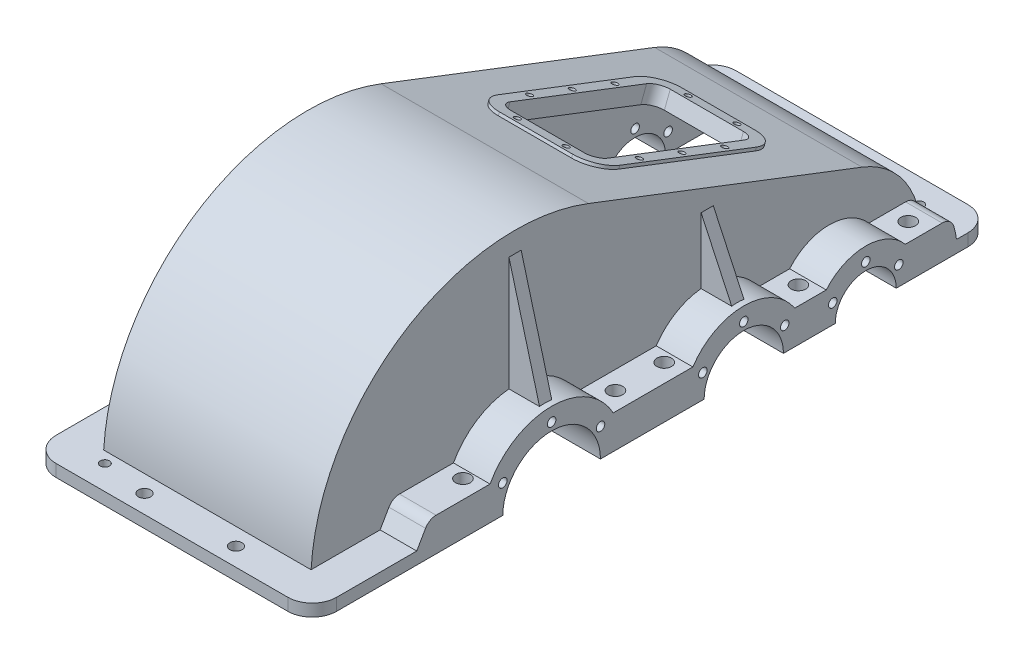
SolidWorks part; units mm, degrees
material "Cast Alloy Steel"
ref_plane "Front Plane" through (0, 0, 0) normal (0, 0, 1) x (1, 0, 0)
ref_plane "Top Plane" through (0, 0, 0) normal (0, 1, 0) x (1, 0, 0)
ref_plane "Right Plane" through (0, 0, 0) normal (1, 0, 0) x (0, 0, -1)
sketch "Sketch1" plane through (0, 0, 0) normal (1, 0, 0) x (0, 0, -1)
  line L0 (-500, 0) -> (500, 0)
  line L1 (403.8835, 139.9877) -> (-44.6602, 312.6393)
  arc A0 (500, 0) -> (403.8835, 139.9877) centre (350, 0) ccw
  arc A1 (-44.6602, 312.6393) -> (-500, 0) centre (-165, 0) ccw
  point P7 (0, 0)
  point P8 (436.4106, 249.0469)
  point P9 (0, 0)
  point P10 (0, 0)
  dimension "D3" = 150
  dimension "D4" = 335
  dimension "D1" = 165
  dimension "D2" = 350
extrude "Boss-Extrude1" add sketch "Sketch1" along normal mid plane 340
shell "Shell1" thickness 21.8
sketch "Sketch2" plane through (0, 0, 0) normal (0, -1, 0) x (1, 0, 0)
  line L0 (-148.2, 478.2) -> (-148.2, -478.2) construction
  line L1 (-230, -557.5) -> (230, -557.5)
  line L2 (-230, -557.5) -> (-230, 557.5)
  line L3 (-230, 557.5) -> (230, 557.5)
  line L4 (230, -557.5) -> (230, 557.5)
  line L5 (-230, -557.5) -> (230, 557.5) construction
  line L6 (-230, 557.5) -> (230, -557.5) construction
  line L7 (148.2, 478.2) -> (148.2, -478.2) construction
  line L8 (148.2, -478.2) -> (-148.2, -478.2) construction
  line L9 (148.2, 478.2) -> (-148.2, 478.2) construction
  line L10 (-148.2, 478.2) -> (-148.2, -478.2)
  line L11 (148.2, 478.2) -> (148.2, -478.2)
  line L12 (148.2, -478.2) -> (-148.2, -478.2)
  line L13 (148.2, 478.2) -> (-148.2, 478.2)
  point P0 (0, 0)
  line M3 (-170, 500) -> (-170, -500)
  line M4 (-170, -500) -> (170, -500)
  line M5 (170, -500) -> (170, 500)
  line M6 (170, 500) -> (-170, 500)
  line M7 (-148.2, -478.2) -> (-148.2, 478.2)
  line M8 (-148.2, 478.2) -> (148.2, 478.2)
  line M9 (148.2, 478.2) -> (148.2, -478.2)
  line M10 (148.2, -478.2) -> (-148.2, -478.2)
  dimension "D1" = 1115
  dimension "D2" = 460
extrude "Boss-Extrude4" add sketch "Sketch2" against normal blind 20 contours M6 M3 M4 M5 M10 M7 M8 M9 | L1 L4 L3 L2 M3 M6 M5 M4
fillet "Fillet1" radius 40 4 edges at (-230, 10, -557.5) (-230, 10, 557.5) (230, 10, -557.5) (230, 10, 557.5)
sketch "Sketch6" plane through (0, 0, 0) normal (1, 0, 0) x (0, 0, -1)
  line L0 (517.5, 0) -> (-517.5, 0) construction
  circle A0 centre (-165, 0) radius 80
  circle A1 centre (150, 0) radius 65
  circle A2 centre (350, 0) radius 50
  dimension "D1" = 160
  dimension "D2" = 130
  dimension "D3" = 100
  dimension "D4" = 165
  dimension "D5" = 350
  dimension "D6" = 200
extrude "Cut-Extrude2" cut sketch "Sketch6" against normal through all both and the other way through all
sketch "Sketch7" plane through (0, 0, 0) normal (1, 0, 0) x (0, 0, -1)
  line L0 (395.8258, 20) -> (498.6607, 20) construction
  line L1 (211.8466, 20) -> (304.1742, 20) construction
  line L2 (88.1534, 20) -> (-87.5403, 20) construction
  line L3 (-499.4025, 20) -> (-242.4597, 20) construction
  line L4 (395.8258, 20) -> (498.6607, 20)
  line L5 (211.8466, 20) -> (304.1742, 20)
  line L6 (88.1534, 20) -> (-87.5403, 20)
  line L7 (-386.2023, 20) -> (-242.4597, 20)
  line L8 (-365.995, 55) -> (-265.995, 55)
  line L9 (66.4835, 55) -> (-64.005, 55)
  line L10 (233.5165, 55) -> (285.1926, 55)
  line L11 (414.8074, 55) -> (489.5529, 55)
  line L12 (-365.995, 55) -> (-386.2023, 20)
  line L13 (-499.4025, 55) -> (-265.995, 55) construction
  line L14 (-499.4025, 20) -> (-242.4597, 20) construction
  line L15 (414.8074, 55) -> (498.6607, 55) construction
  line L16 (-242.4597, 20) -> (-517.5, 20) construction
  arc A0 (498.6607, 20) -> (403.8835, 139.9877) centre (350, 0) ccw construction
  arc A1 (395.8258, 20) -> (304.1742, 20) centre (350, 0) ccw construction
  arc A2 (211.8466, 20) -> (88.1534, 20) centre (150, 0) ccw construction
  arc A3 (-87.5403, 20) -> (-242.4597, 20) centre (-165, 0) ccw construction
  arc A4 (498.6607, 20) -> (489.5529, 55) centre (350, 0) ccw
  arc A5 (395.8258, 20) -> (304.1742, 20) centre (350, 0) ccw
  arc A6 (211.8466, 20) -> (88.1534, 20) centre (150, 0) ccw
  arc A7 (-87.5403, 20) -> (-242.4597, 20) centre (-165, 0) ccw
  arc A8 (-64.005, 55) -> (-265.995, 55) centre (-165, 0) ccw
  arc A9 (233.5165, 55) -> (66.4835, 55) centre (150, 0) ccw
  arc A10 (414.8074, 55) -> (285.1926, 55) centre (350, 0) ccw
  point P26 (-394.0327, 20)
  dimension "D2" = 60
  dimension "D3" = 100
  dimension "D1" = 35
extrude "Boss-Extrude5" add sketch "Sketch7" against normal up to surface (60 mm away) from surface at 230 up to face at (170, 87.5999, -97.0662) starting at face at (230, 10.051, -0.1155)
sketch "Sketch8" plane through (0, 20, 0) normal (0, 1, 0) x (1, 0, 0)
  line L0 (200, 524.3283) -> (200, -465.5786) construction
  line L1 (230, 414.8074) -> (230, 489.5529) construction
  line L3 (170, 489.5529) -> (230, 489.5529) construction
  circle A0 centre (200, 449.5529) radius 12
  circle A1 centre (200, 269.5529) radius 12
  circle A2 centre (200, 49.5529) radius 12
  circle A3 centre (200, -30.4471) radius 12
  circle A4 centre (200, -280.4471) radius 12
  dimension "D3" = 24
  dimension "D5" = 24
  dimension "D6" = 24
  dimension "D8" = 24
  dimension "D10" = 24
  dimension "D1" = 30
  dimension "D2" = 40
  dimension "D4" = 180
  dimension "D7" = 220
  dimension "D9" = 80
  dimension "D11" = 250
extrude "Cut-Extrude3" cut sketch "Sketch8" against normal up to surface (20 mm away) and the other way through all up to face at (189.1, 0, -257.5)
fillet "Fillet2" radius 20 2 edges at (200, 55, -489.5529) (200, 55, 365.995)
sketch "Sketch9" plane through (0, 20, 0) normal (0, 1, 0) x (1, 0, 0)
  line L0 (75, 527.5) -> (75, -527.5) construction
  line L1 (-190, 557.5) -> (190, 557.5) construction
  line L2 (-190, -557.5) -> (190, -557.5) construction
  circle A0 centre (75, 527.5) radius 10
  circle A1 centre (75, -527.5) radius 10
  dimension "D4" = 20
  dimension "D1" = 75
  dimension "D2" = 30
  dimension "D3" = 30
extrude "Cut-Extrude4" cut sketch "Sketch9" against normal up to surface (20 mm away) up to face at (200, 0, -257.5529)
sketch "Sketch10" plane through (0, 20, 0) normal (0, 1, 0) x (1, 0, 0)
  line L0 (230, 517.5) -> (230, 498.6607) construction
  line L1 (-190, 557.5) -> (190, 557.5) construction
  circle A0 centre (150, 517.5) radius 7.5
  circle A1 centre (-150, -517.5) radius 7.5
  point P11 (0, 0)
  dimension "D1" = 15
  dimension "D2" = 80
  dimension "D3" = 40
  dimension "D4" = 2
sketch "Sketch11" plane through (0, 0, 0) normal (0, 1, 0) x (1, 0, 0)
  line L0 (0, 0) -> (-447.3821, 0)
  line L2 (0, 626.9048) -> (-421.736, 626.9048)
  line L3 (0, 626.9048) -> (0, -604.1083)
  line L4 (0, -604.1083) -> (-421.736, -604.1083)
  line L5 (-421.736, 626.9048) -> (-421.736, -604.1083)
extrude "Cut-Extrude6" cut sketch "Sketch11" against normal through all both and the other way through all contours L2 L5 L0 L3 | L0 L5 L4 L3
mirror "Mirror1" about plane through (0, 0, 0) normal (-1, 0, 0) of bodies 114
extrude "Cut-Extrude7" cut sketch "Sketch10" against normal through all both and the other way through all
sketch "Sketch12" plane through (230, 0, 0) normal (1, 0, 0) x (0, 0, -1)
  circle A0 centre (-165, 0) radius 92.5 construction
  circle A1 centre (150, 0) radius 77.5 construction
  circle A2 centre (350, 0) radius 62.5 construction
  circle A3 centre (-165, 92.5) radius 7
  circle A4 centre (-84.8927, 46.25) radius 7
  circle A5 centre (-84.8927, -46.25) radius 7
  circle A6 centre (-165, -92.5) radius 7
  circle A7 centre (-245.1073, -46.25) radius 7
  circle A8 centre (-245.1073, 46.25) radius 7
  circle A9 centre (150, 77.5) radius 7
  circle A10 centre (217.117, 38.75) radius 7
  circle A11 centre (217.117, -38.75) radius 7
  circle A12 centre (150, -77.5) radius 7
  circle A13 centre (82.883, -38.75) radius 7
  circle A14 centre (82.883, 38.75) radius 7
  circle A15 centre (350, 62.5) radius 7
  circle A16 centre (404.1266, 31.25) radius 7
  circle A17 centre (404.1266, -31.25) radius 7
  circle A18 centre (350, -62.5) radius 7
  circle A19 centre (295.8734, -31.25) radius 7
  circle A20 centre (295.8734, 31.25) radius 7
  point P24 (-165, 0)
  point P37 (150, 0)
  point P50 (350, 0)
  dimension "D1" = 185
  dimension "D2" = 155
  dimension "D3" = 125
  dimension "D4" = 14
  dimension "D6" = 14
  dimension "D8" = 14
  dimension "D5" = 6
  dimension "D7" = 6
  dimension "D9" = 6
extrude "Cut-Extrude8" cut sketch "Sketch12" against normal through all both and the other way through all
ref_plane "Plane1" through (0, 0, 165) normal (0, 0, 1) x (1, 0, 0)
ref_plane "Plane2" through (0, 0, -150) normal (0, 0, 1) x (1, 0, 0)
sketch "Sketch13" plane through (0, 0, 165) normal (0, 0, 1) x (1, 0, 0)
  line L0 (220, 115) -> (170, 301.6025)
  line L1 (230, 115) -> (170, 115) construction
  line L2 (170, 20) -> (170, 335) construction
  line L3 (230, 55) -> (230, 115) construction
  dimension "D1" = 10
  dimension "D2" = 75
rib "Rib1" sketch "Sketch13" sketch "Sketch13" thickness 20 extrusion direction parallel to sketch draft on no parameters "D1"=20
sketch "Sketch14" plane through (0, 0, -150) normal (0, 0, 1) x (1, 0, 0)
  line L0 (220, 100) -> (169.7975, 207.6595)
  line L1 (230, 100) -> (170, 100) construction
  point P5 (0, 0)
  dimension "D1" = 10
  dimension "D2" = 65
rib "Rib2" sketch "Sketch14" sketch "Sketch14" thickness 20 extrusion direction parallel to sketch draft on no parameters "D1"=20
mirror "Mirror2" about plane through (0, 0, 0) normal (1, 0, 0) of "Rib2", "Rib1"
sketch "Sketch15" plane through (0, 257.3238, -99.048) normal (0, 0.9333, -0.3592) x (1, 0, 0)
  line L0 (0, 326.6381) -> (0, -153.9865) construction
  line L1 (170, 326.6381) -> (-170, 326.6381) construction
  line L2 (170, -153.9865) -> (-170, -153.9865) construction
  line L3 (170, 94.229) -> (-170, 94.229) construction
  line L4 (170, 74.8801) -> (170, 113.578) construction
  line L5 (-170, 113.578) -> (-170, 74.8801) construction
  line L7 (-80, -45.771) -> (80, -45.771)
  line L8 (-80, -45.771) -> (-80, 234.229)
  line L9 (-80, 234.229) -> (80, 234.229)
  line L10 (80, -45.771) -> (80, 234.229)
  line L11 (-80, -45.771) -> (80, 234.229) construction
  line L12 (-80, 234.229) -> (80, -45.771) construction
  point P12 (0, 94.229)
  dimension "D1" = 160
  dimension "D2" = 280
extrude "Cut-Extrude9" cut sketch "Sketch15" against normal up to surface and the other way through all
fillet "Fillet3" radius 20 4 edges at (80, 263.5933, -52.4166) (-80, 263.5933, -52.4166) (80, 163.0108, -313.7271) (-80, 163.0108, -313.7271)
sketch "Sketch17" plane through (0, 257.3238, -99.048) normal (0, 0.9333, -0.3592) x (1, 0, 0)
  line L0 (-80, -25.771) -> (-80, 214.229) construction
  line L1 (80, 214.229) -> (80, -25.771) construction
  line L3 (60, -45.771) -> (-60, -45.771) construction
  line L4 (-60, 234.229) -> (60, 234.229) construction
  line L5 (-80, -25.771) -> (-80, 214.229)
  line L6 (60, -45.771) -> (-60, -45.771)
  line L7 (80, 214.229) -> (80, -25.771)
  line L8 (-60, 234.229) -> (60, 234.229)
  line L9 (-100, -25.771) -> (-100, 214.229)
  line L10 (-60, 254.229) -> (60, 254.229)
  line L11 (100, 214.229) -> (100, -25.771)
  line L12 (60, -65.771) -> (-60, -65.771)
  arc A0 (-60, 234.229) -> (-80, 214.229) centre (-60, 214.229) ccw construction
  arc A1 (-80, -25.771) -> (-60, -45.771) centre (-60, -25.771) ccw construction
  arc A2 (60, -45.771) -> (80, -25.771) centre (60, -25.771) ccw construction
  arc A3 (80, 214.229) -> (60, 234.229) centre (60, 214.229) ccw construction
  arc A4 (-60, 234.229) -> (-80, 214.229) centre (-60, 214.229) ccw
  arc A5 (-80, -25.771) -> (-60, -45.771) centre (-60, -25.771) ccw
  arc A6 (60, -45.771) -> (80, -25.771) centre (60, -25.771) ccw
  arc A7 (80, 214.229) -> (60, 234.229) centre (60, 214.229) ccw
  arc A8 (-60, 254.229) -> (-100, 214.229) centre (-60, 214.229) ccw
  arc A9 (100, 214.229) -> (60, 254.229) centre (60, 214.229) ccw
  arc A10 (60, -65.771) -> (100, -25.771) centre (60, -25.771) ccw
  arc A11 (-100, -25.771) -> (-60, -65.771) centre (-60, -25.771) ccw
  dimension "D1" = 20
extrude "Boss-Extrude6" add sketch "Sketch17" along normal blind 5
sketch "Sketch18" plane through (0, 261.99, -100.8441) normal (0, 0.9333, -0.3592) x (1, 0, 0)
  line L20 (0, -129.0902) -> (0, 317.5483) construction
  line L21 (0, 94.229) -> (90, 94.229) construction
  line L24 (-60, -55.771) -> (60, -55.771)
  line L25 (90, -25.771) -> (90, 214.229)
  line L26 (60, 244.229) -> (-60, 244.229)
  line L27 (-90, 214.229) -> (-90, -25.771)
  line L28 (-60, -55.771) -> (60, -55.771) construction
  line L29 (90, -25.771) -> (90, 214.229) construction
  line L30 (60, 244.229) -> (-60, 244.229) construction
  line L31 (-90, 214.229) -> (-90, -25.771) construction
  circle A16 centre (40, 244.229) radius 5
  circle A17 centre (90, 169.229) radius 5
  circle A18 centre (90, 94.229) radius 5
  circle A19 centre (90, 19.229) radius 5
  arc A20 (-90, -25.771) -> (-60, -55.771) centre (-60, -25.771) ccw
  arc A21 (60, -55.771) -> (90, -25.771) centre (60, -25.771) ccw
  arc A22 (90, 214.229) -> (60, 244.229) centre (60, 214.229) ccw
  arc A23 (-60, 244.229) -> (-90, 214.229) centre (-60, 214.229) ccw
  arc A24 (-90, -25.771) -> (-60, -55.771) centre (-60, -25.771) ccw construction
  arc A25 (60, -55.771) -> (90, -25.771) centre (60, -25.771) ccw construction
  arc A26 (90, 214.229) -> (60, 244.229) centre (60, 214.229) ccw construction
  arc A27 (-60, 244.229) -> (-90, 214.229) centre (-60, 214.229) ccw construction
  circle A28 centre (40, -55.771) radius 5
  circle A29 centre (-40, -55.771) radius 5
  circle A30 centre (-90, 19.229) radius 5
  circle A31 centre (-90, 94.229) radius 5
  circle A32 centre (-90, 169.229) radius 5
  circle A33 centre (-40, 244.229) radius 5
  point P13 (0, 94.229)
  dimension "D2" = 10
  dimension "D3" = 40
  dimension "D4" = 40
  dimension "D5" = 75
  dimension "D6" = 75
  dimension "D1" = 10
extrude "Cut-Extrude10" cut sketch "Sketch18" against normal up to surface (5 mm away) contours A29
